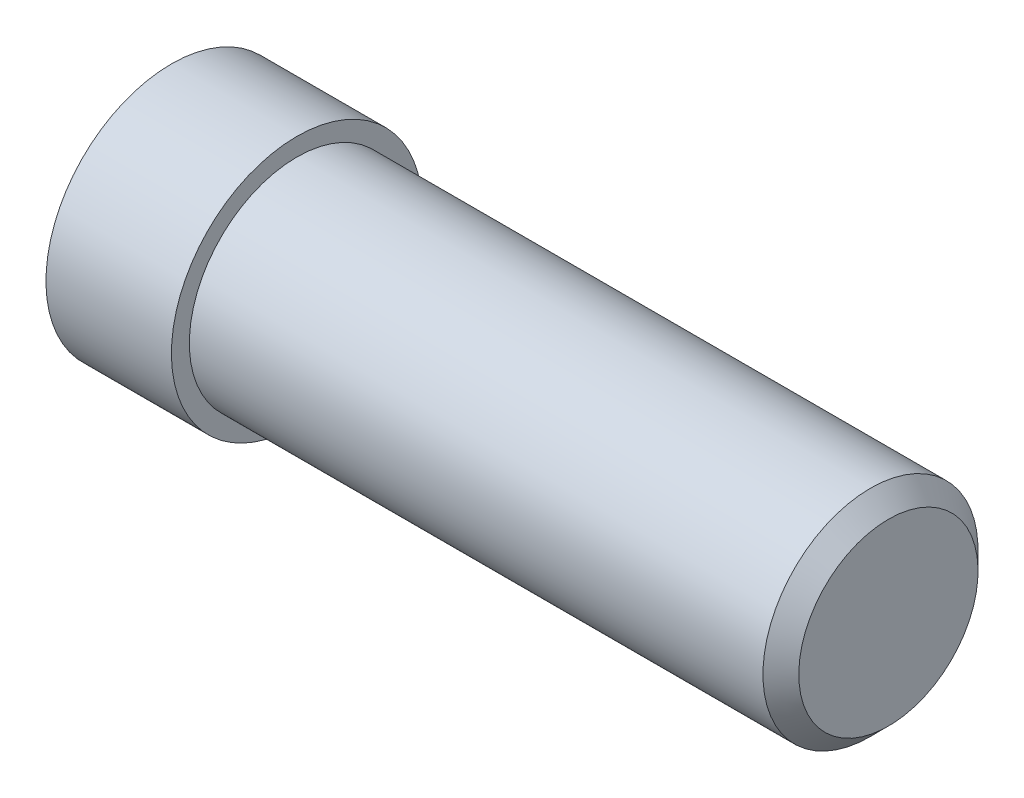
SolidWorks part; units mm, degrees
ref_plane "Front Plane" through (0, 0, 0) normal (0, 0, 1) x (1, 0, 0)
ref_plane "Top Plane" through (0, 0, 0) normal (0, 1, 0) x (1, 0, 0)
ref_plane "Right Plane" through (0, 0, 0) normal (1, 0, 0) x (0, 0, -1)
sketch "Sketch1" plane through (0, 0, 0) normal (0, 0, 1) x (1, 0, 0)
  line L0 (0, 0) -> (-40, 0)
  line L1 (-40, 0) -> (-40, 7)
  line L2 (-40, 7) -> (-33, 7)
  line L3 (-33, 7) -> (-33, 6)
  line L4 (-33, 6) -> (0, 6)
  line L5 (0, 6) -> (0, 0)
  dimension "D1" = 33
  dimension "D2" = 7
  dimension "D3" = 6
  dimension "D4" = 7
revolve "Revolve1" add sketch "Sketch1" angle 360 about L0
chamfer "Chamfer1" distance 1 angle 45 1 edges at (0, 6, 0)
